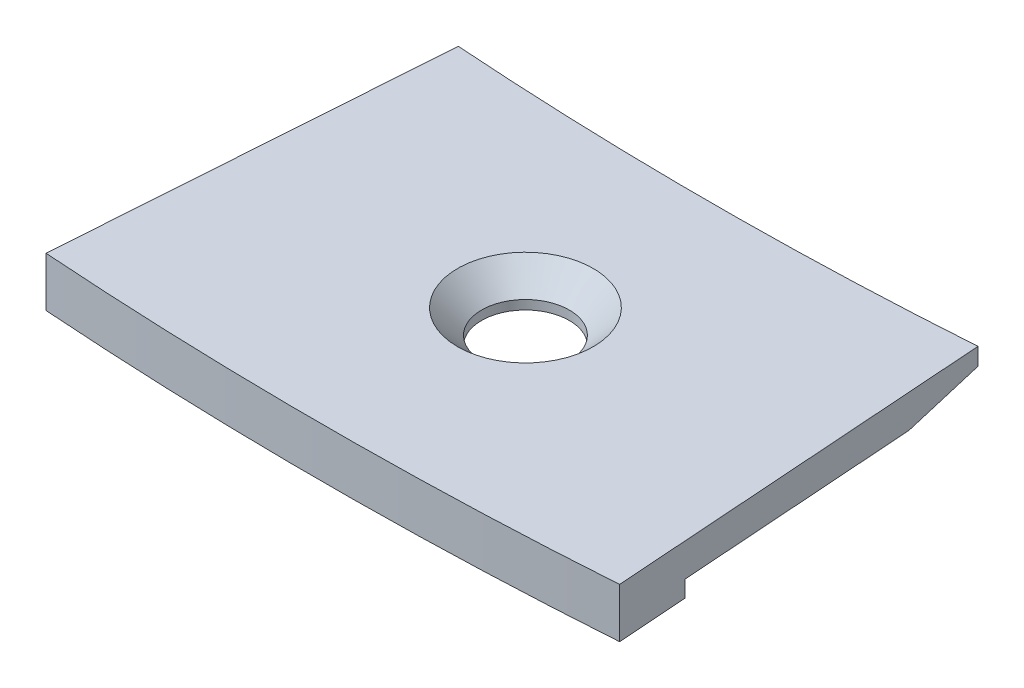
SolidWorks part; units mm, degrees
ref_plane "Front Plane" through (0, 0, 0) normal (0, 0, 1) x (1, 0, 0)
ref_plane "Top Plane" through (0, 0, 0) normal (0, 1, 0) x (1, 0, 0)
ref_plane "Right Plane" through (0, 0, 0) normal (1, 0, 0) x (0, 0, -1)
sketch "BASE" plane through (0, 0, 0) normal (0, 1, 0) x (1, 0, 0)
  line L0 (0, 0) -> (0, -243.5) construction
  line L1 (15.9742, -228.4422) -> (16.9857, -242.9068)
  line L2 (-15.9742, -228.4422) -> (-16.9857, -242.9068)
  line L3 (0, 0) -> (15.9742, -228.4422) construction
  line L4 (0, 0) -> (-15.9742, -228.4422) construction
  line L5 (0, -229) -> (0, -243.5) construction
  line L7 (-10, -226.25) -> (10, -226.25) construction
  line L8 (-10, -226.25) -> (-10, -246.25) construction
  line L9 (-10, -246.25) -> (10, -246.25) construction
  line L10 (10, -226.25) -> (10, -246.25) construction
  line L11 (-10, -226.25) -> (10, -246.25) construction
  line L12 (-10, -246.25) -> (10, -226.25) construction
  arc A0 (-16.9857, -242.9068) -> (16.9857, -242.9068) centre (0, 0) ccw
  arc A1 (-15.9742, -228.4422) -> (15.9742, -228.4422) centre (0, 0) ccw
  circle A2 centre (0, -236.25) radius 2.65
  dimension "D1" = 487
  dimension "D2" = 14.5
  dimension "D6" = 5.3
  dimension "D3" = 4
  dimension "D4" = 4
  dimension "D5" = 20
sketch "Sketch2" plane through (0, 0, 0) normal (0, 1, 0) x (1, 0, 0)
  line L1 (-15.9742, -228.4422) -> (-16.9857, -242.9068) construction
  line L3 (15.9742, -228.4422) -> (16.9857, -242.9068) construction
  line L4 (0, 0) -> (-17.3345, -247.8947) construction
  line L5 (0, 0) -> (17.3345, -247.8947) construction
  line L6 (-15.9847, -228.5918) -> (-17.3345, -247.8947)
  line L7 (15.9847, -228.5918) -> (17.3345, -247.8947)
  arc A0 (15.9847, -228.5918) -> (-15.9847, -228.5918) centre (0, 0) cw
  arc A1 (-15.9742, -228.4422) -> (15.9742, -228.4422) centre (0, 0) ccw construction
  arc A2 (17.3345, -247.8947) -> (-17.3345, -247.8947) centre (0, 0) cw
  arc A3 (-16.9857, -242.9068) -> (16.9857, -242.9068) centre (0, 0) ccw construction
  circle A4 centre (0, -236.25) radius 2.65
  dimension "D1" = 0.15
  dimension "D2" = 5
  dimension "D3" = 5.3
extrude "Boss-Extrude1" add sketch "Sketch2" along normal blind 2
sketch "Sketch3" plane through (0, 0, 0) normal (0, 1, 0) x (1, 0, 0)
  line L0 (0, 0) -> (15.9742, -228.4422) construction
  line L1 (0, 0) -> (-15.9742, -228.4422) construction
  line L2 (-15.7057, -224.6015) -> (-15.9847, -228.5918)
  line L3 (15.7057, -224.6015) -> (15.9847, -228.5918)
  arc A0 (15.9847, -228.5918) -> (-15.9847, -228.5918) centre (0, 0) cw
  arc A1 (15.7057, -224.6015) -> (-15.7057, -224.6015) centre (0, 0) cw
  dimension "D1" = 4
extrude "Boss-Extrude2" add sketch "Sketch3" against normal blind 2 from surface at 2 starting at face at (0, 2, 238.5341)
chamfer "Chamfer1" distance 4.5 angle 12 1 edges at (0, 0, 225.15)
sketch "Sketch4" plane through (0, 0, 0) normal (0, -1, 0) x (1, 0, 0)
  line L0 (15.9742, 228.4422) -> (16.9857, 242.9068) construction
  line L1 (-16.0196, 229.0906) -> (-17.3345, 247.8947) construction
  line L2 (17.3345, 247.8947) -> (16.0196, 229.0906) construction
  line L3 (-17.3345, 247.8947) -> (-17.038, 243.655)
  line L4 (17.3345, 247.8947) -> (17.038, 243.655)
  arc A0 (-17.038, 243.655) -> (17.038, 243.655) centre (0, 0) cw
  arc A1 (-17.3345, 247.8947) -> (17.3345, 247.8947) centre (0, 0) cw
  arc A2 (16.9857, 242.9068) -> (-16.9857, 242.9068) centre (0, 0) ccw construction
  arc A3 (17.3345, 247.8947) -> (-17.3345, 247.8947) centre (0, 0) ccw construction
  point P13 (0, 0)
  dimension "D2" = 0.75
extrude "Boss-Extrude3" add sketch "Sketch4" along normal blind 1
sketch "Sketch18" plane through (0, 2, 0) normal (0, 1, 0) x (1, 0, 0)
  circle A0 centre (0, -236.25) radius 4.225
  dimension "D1" = 8.45
hole_wizard "CSK for M3.5 Flat Head Machine Screw2" positions "Sketch19" profile "Sketch20" countersink size "M3.5" standard "ANSI Metric" end condition up to next
sketch "Sketch19" plane through (0, 2, 0) normal (0, 1, 0) x (1, 0, 0)
  point P0 (0, -236.25)
sketch "Sketch20" plane through (0, 2, 236.25) normal (1, 0, 0) x (0, 0, 1)
  line L0 (0, 0) -> (0, 3)
  line L1 (0, 3) -> (1.85, 3)
  line L2 (1.85, 3) -> (1.85, 2.25)
  line L3 (1.85, 2.25) -> (4.1, 0)
  line L5 (4.1, 0) -> (0, 0)
  line L6 (-1.85, 2.25) -> (-4.1, 0) construction
  line L11 (0, -6.35) -> (0, 107.95) construction
  dimension "Thru Hole Dia." = 3.7
  dimension "Thru Hole Depth" = 3
  dimension "Near C'Sink Dia." = 8.2
  dimension "Near C'Sink Angle" = 90
